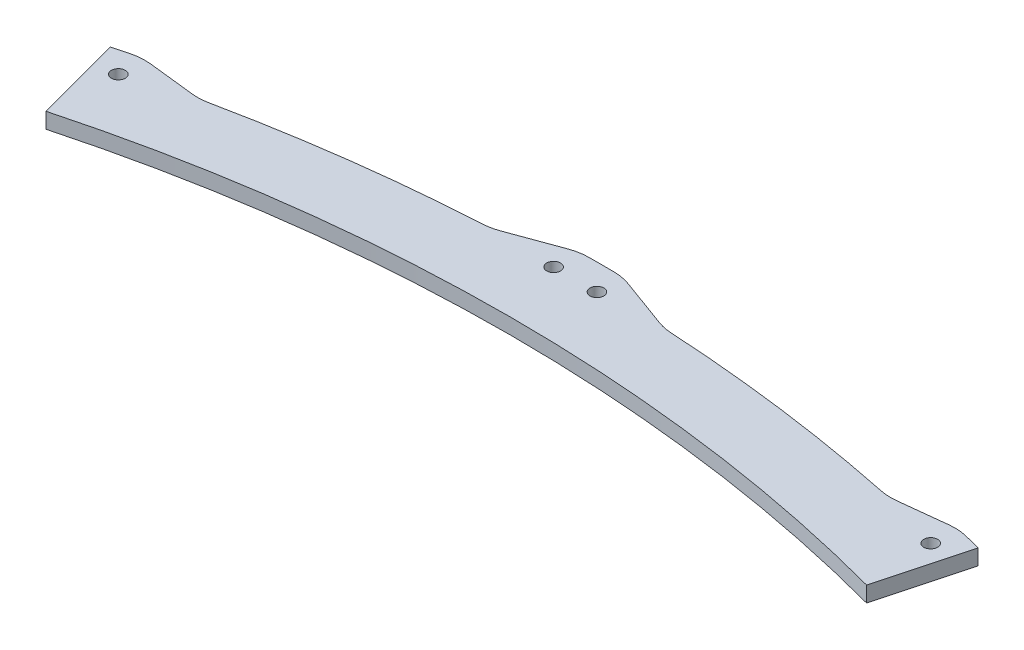
SolidWorks part; units mm, degrees
ref_plane "Front Plane" through (0, 0, 0) normal (0, 0, 1) x (1, 0, 0)
ref_plane "Top Plane" through (0, 0, 0) normal (0, 1, 0) x (1, 0, 0)
ref_plane "Right Plane" through (0, 0, 0) normal (1, 0, 0) x (0, 0, -1)
sketch "Sketch1" plane through (0, 0, 0) normal (0, 1, 0) x (1, 0, 0)
  line L0 (0, 0) -> (-280.8187, 1048.0295)
  line L1 (-280.8187, 1085) -> (280.8187, 1085) construction
  line L2 (-280.8187, 1085) -> (-280.8187, 785) construction
  line L3 (-280.8187, 785) -> (280.8187, 785) construction
  line L4 (280.8187, 1085) -> (280.8187, 785) construction
  line L5 (0, 0) -> (280.8187, 1048.0295)
  line L6 (0, 1020) -> (0, 0) construction
  line L7 (-12.5, 967.4192) -> (-50, 953.6902)
  line L8 (12.5, 967.4192) -> (50, 953.6902)
  line L9 (955, 0) -> (1000, 0) construction
  line L10 (1000, 0) -> (1045, 0) construction
  line L11 (-235.8884, 938.3032) -> (-198.5369, 934.1349)
  line L12 (235.8884, 938.3032) -> (198.5369, 934.1349)
  circle A0 centre (0, 0) radius 1085
  circle A1 centre (0, 0) radius 1045
  circle A2 centre (0, 0) radius 955
  circle A3 centre (0, 0) radius 915
  circle A6 centre (0, 0) radius 1065 construction
  circle A7 centre (0, 0) radius 935 construction
  circle A12 centre (0, 0) radius 1032.5 construction
  circle A15 centre (0, 0) radius 1000 construction
  circle A16 centre (0, 0) radius 967.5 construction
  arc A17 (-12.5, 967.4192) -> (12.5, 967.4192) centre (0, 0) cw
  circle A18 centre (-12.5, 952.5) radius 4
  circle A19 centre (12.5, 952.5) radius 4
  arc A20 (-250.4074, 934.5332) -> (-235.8884, 938.3032) centre (0, 0) cw
  circle A21 centre (-234.4298, 923.2004) radius 4
  circle A22 centre (234.4298, 923.2004) radius 4
  arc A23 (250.4074, 934.5332) -> (235.8884, 938.3032) centre (0, 0) ccw
  point P12 (0, 785)
  dimension "D8" = 2000
  dimension "D12" = 8
  dimension "D19" = 8
  dimension "D1" = 300
  dimension "D3" = 40
  dimension "D4" = 40
  dimension "D5" = 20
  dimension "D6" = 20
  dimension "D7" = 170
  dimension "D2" = 15
  dimension "D13" = 15
  dimension "D14" = 12.5
  dimension "D9" = 12.5
  dimension "D10" = 12.5
  dimension "D11" = 50
  dimension "D15" = 12.5
  dimension "D16" = 952.5
  dimension "D17" = 15
  dimension "D18" = 50
  dimension "D20" = 12.5
  dimension "D21" = 952.5
extrude "Boss-Extrude1" add sketch "Sketch1" along normal blind 9
fillet "Fillet1" radius 30 8 edges at (235.8884, 4.5, -938.3032) (198.5369, 4.5, -934.1349) (50, 4.5, -953.6902) (12.5, 4.5, -967.4192) (-12.5, 4.5, -967.4192) (-50, 4.5, -953.6902) (-198.5369, 4.5, -934.1349) (-235.8884, 4.5, -938.3032)
equation "\"D16@Sketch1\"=1910/2-2.5"
equation "\"D21@Sketch1\"=1910/2-2.5"
